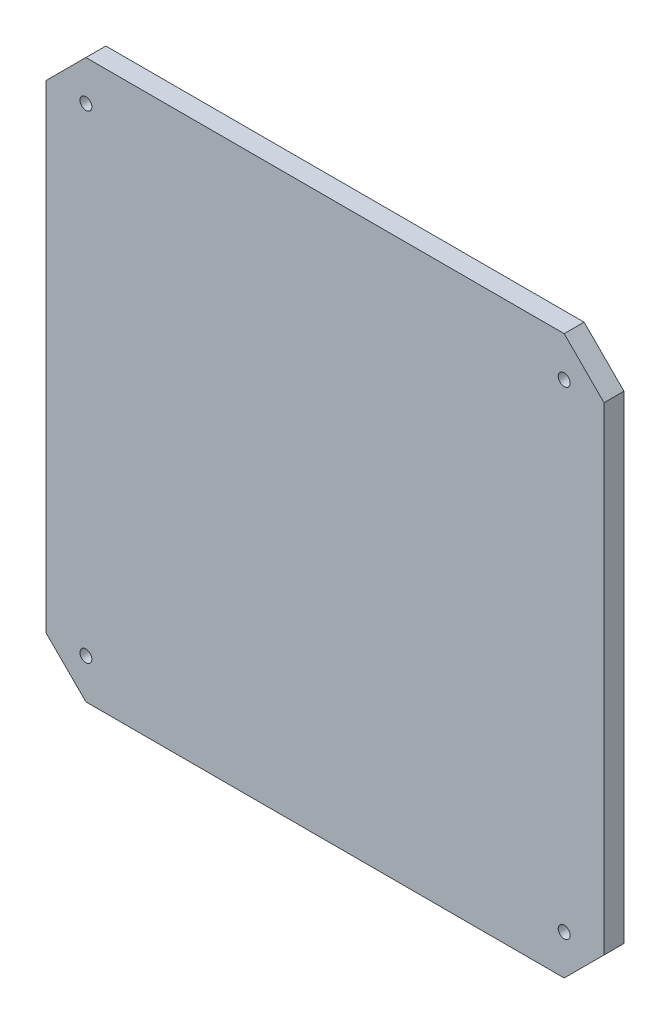
SolidWorks part; units mm, degrees
ref_plane "Front Plane" through (0, 0, 0) normal (0, 0, 1) x (1, 0, 0)
ref_plane "Top Plane" through (0, 0, 0) normal (0, 1, 0) x (1, 0, 0)
ref_plane "Right Plane" through (0, 0, 0) normal (1, 0, 0) x (0, 0, -1)
sketch "Sketch1" plane through (0, 0, 0) normal (0, 0, 1) x (1, 0, 0)
  line L0 (-177.8, 152.4) -> (-152.4, 177.8)
  line L1 (-152.4, 177.8) -> (152.4, 177.8)
  line L2 (-177.8, 152.4) -> (-177.8, -152.4)
  line L3 (-152.4, -177.8) -> (152.4, -177.8)
  line L4 (177.8, 152.4) -> (177.8, -152.4)
  line L5 (-177.8, 177.8) -> (177.8, -177.8) construction
  line L6 (-177.8, -177.8) -> (177.8, 177.8) construction
  line L7 (152.4, 177.8) -> (177.8, 152.4)
  line L8 (152.4, -177.8) -> (177.8, -152.4)
  line L9 (-177.8, -152.4) -> (-152.4, -177.8)
  line L10 (-152.4, 152.4) -> (152.4, 152.4) construction
  line L11 (152.4, 152.4) -> (152.4, -152.4) construction
  line L12 (152.4, -152.4) -> (-152.4, -152.4) construction
  line L13 (-152.4, -152.4) -> (-152.4, 152.4) construction
  circle A0 centre (-152.4, 152.4) radius 3.81
  circle A1 centre (152.4, 152.4) radius 3.81
  circle A2 centre (152.4, -152.4) radius 3.81
  circle A3 centre (-152.4, -152.4) radius 3.81
  point P0 (0, 0)
  dimension "D4" = 7.62
  dimension "D1" = 355.6
  dimension "D2" = 25.4
  dimension "D3" = 25.4
extrude "Boss-Extrude1" add sketch "Sketch1" along normal blind 12.7
